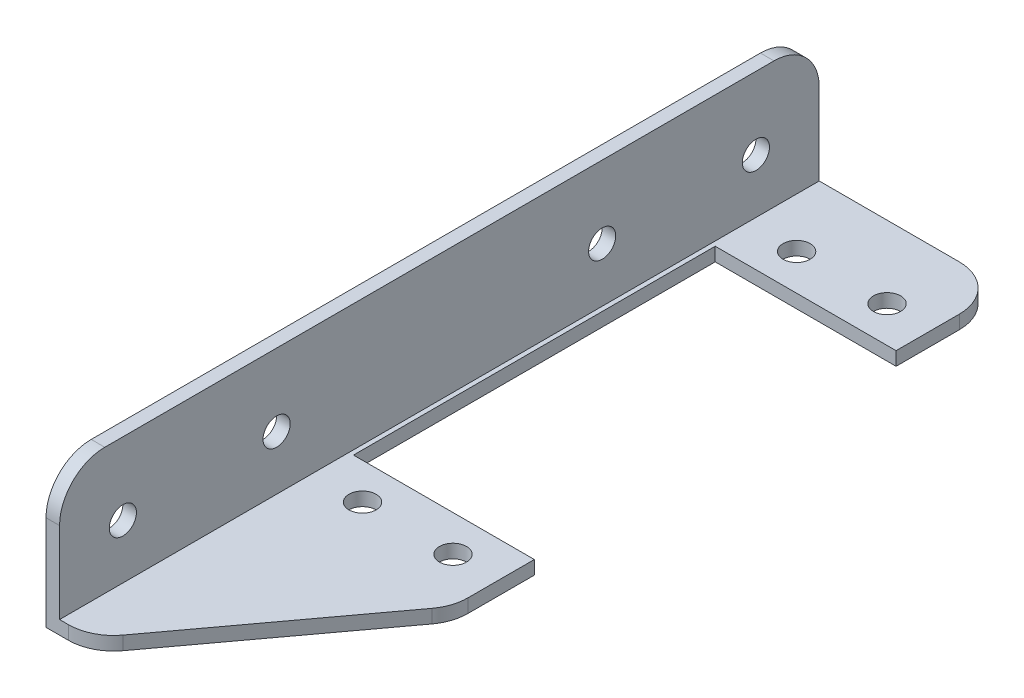
SolidWorks part; units mm, degrees
material "3.0205 (EN-AW 1200)"
ref_plane "Plan de face" through (0, 0, 0) normal (0, 0, 1) x (1, 0, 0)
ref_plane "Plan de dessus" through (0, 0, 0) normal (0, 1, 0) x (1, 0, 0)
ref_plane "Plan de droite" through (0, 0, 0) normal (1, 0, 0) x (0, 0, -1)
sketch "Esquisse1" plane through (0, 0, 0) normal (0, 0, 1) x (1, 0, 0)
  line L0 (0, 15.5) -> (0, 0)
  line L1 (0, 0) -> (27.5, 0)
  dimension "D1" = 15.5
  dimension "D2" = 27.5
extrude "Extru.-Mince1" add sketch "Esquisse1" along normal blind 84 thin thin type one direction reverse wall 1.5
sketch "Esquisse2" plane through (0, 0, 0) normal (-1, 0, 0) x (0, 0, 1)
  line L0 (42, 15.5) -> (42, 0) construction
  line L1 (84, 15.5) -> (0, 15.5) construction
  line L2 (84, 0) -> (0, 0) construction
  line L3 (0, 15.5) -> (0, 0) construction
  circle A0 centre (7, 7.5) radius 1.5
  circle A1 centre (24, 7.5) radius 1.5
  circle A2 centre (60, 7.5) radius 1.5
  circle A3 centre (77, 7.5) radius 1.5
  dimension "D1" = 3
  dimension "D2" = 70
  dimension "D3" = 7.5
  dimension "D4" = 7
  dimension "D5" = 18
  dimension "D6" = 36
  dimension "D7" = 17
  dimension "D8" = 8
extrude "Enlèv. mat.-Extru.1" cut sketch "Esquisse2" against normal blind 8
sketch "Esquisse3" plane through (0, 0, 0) normal (0, -1, 0) x (1, 0, 0)
  line L0 (27.5, 84) -> (27.5, 0) construction
  line L1 (27.5, 52) -> (2, 52)
  line L2 (27.5, 52) -> (27.5, 12)
  line L3 (27.5, 12) -> (2, 12)
  line L4 (2, 52) -> (2, 12)
  line L5 (2, 32) -> (27.5, 32) construction
  line L6 (0, 84) -> (0, 0) construction
  circle A0 centre (7, 56) radius 1.5
  circle A1 centre (17, 56) radius 1.5
  circle A2 centre (17, 8) radius 1.5
  circle A3 centre (7, 8) radius 1.5
  point P19 (0, 42)
  dimension "D1" = 10
  dimension "D2" = 48
  dimension "D3" = 5
  dimension "D4" = 3
  dimension "D6" = 7
  dimension "D5" = 40
  dimension "D7" = 10
extrude "Enlèv. mat.-Extru.2" cut sketch "Esquisse3" against normal blind 5
sketch "Esquisse4" plane through (0, 0, 0) normal (0, -1, 0) x (1, 0, 0)
  line L0 (0, 0) -> (27.5, 0) construction
  line L1 (27.5, 84) -> (22, 84)
  line L2 (27.5, 84) -> (27.5, 0)
  line L3 (27.5, 0) -> (22, 0)
  line L4 (22, 84) -> (22, 0)
  circle A0 centre (17, 8) radius 1.5 construction
  dimension "D1" = 5
extrude "Enlèv. mat.-Extru.3" cut sketch "Esquisse4" against normal blind 6
chamfer "Chanfrein1" distance 17 distance2 23 1 edges at (22, 0.75, 84)
fillet "Congé1" radius 5 5 edges at (0.75, 15.5, 84) (0.75, 15.5, 0) (22, 0.75, 0) (22, 0.75, 61) (5, 0.75, 84)
